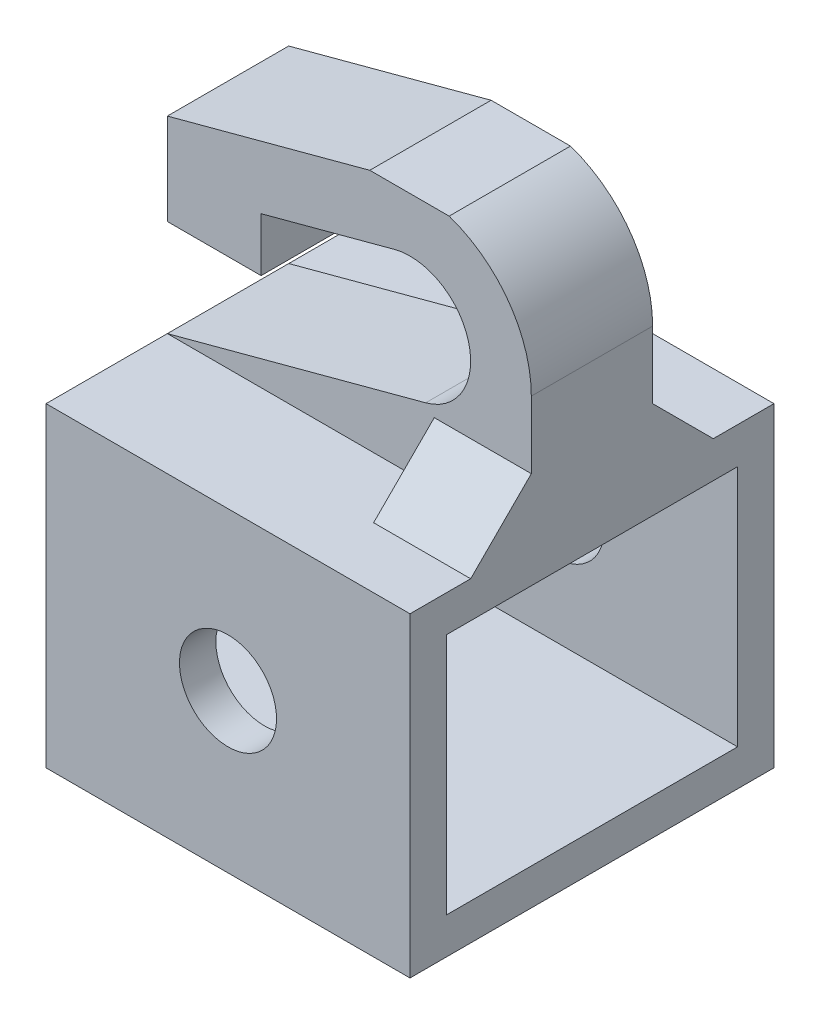
SolidWorks part; units mm, degrees
ref_plane "Front Plane" through (0, 0, 0) normal (0, 0, 1) x (1, 0, 0)
ref_plane "Top Plane" through (0, 0, 0) normal (0, 1, 0) x (1, 0, 0)
ref_plane "Right Plane" through (0, 0, 0) normal (1, 0, 0) x (0, 0, -1)
sketch "Sketch1" plane through (0, 0, 0) normal (0, 1, 0) x (1, 0, 0)
  line L1 (-15, -15) -> (15, -15)
  line L2 (-15, -15) -> (-15, 15)
  line L3 (-15, 15) -> (15, 15)
  line L4 (15, -15) -> (15, 15)
  line L5 (-15, -15) -> (15, 15) construction
  line L6 (-15, 15) -> (15, -15) construction
  point P0 (0, 0)
  dimension "D1" = 30
  dimension "D2" = 30
extrude "Boss-Extrude1" add sketch "Sketch1" along normal blind 26
shell "Shell1" thickness 3
sketch "Sketch3" plane through (0, 0, 15) normal (0, 0, 1) x (1, 0, 0)
  line L0 (-15, 0) -> (15, 26) construction
  line L2 (-15, 26) -> (15, 0) construction
  circle A0 centre (0, 13) radius 4
  dimension "D1" = 8
extrude "Cut-Extrude1" cut sketch "Sketch3" against normal through all
sketch "Sketch4" plane through (0, 0, 0) normal (1, 0, 0) x (0, 0, -1)
  line L0 (-5, 26) -> (5, 26)
  line L1 (5, 26) -> (5, 46)
  line L2 (5, 46) -> (-5, 46)
  line L3 (-5, 46) -> (-5, 26)
  line L6 (-5, 26) -> (5, 46) construction
  line L7 (-5, 46) -> (5, 26) construction
  line L8 (-15, 26) -> (15, 26) construction
  point P4 (0, 36)
  dimension "D1" = 10
  dimension "D3" = 20
extrude "Boss-Extrude4" add sketch "Sketch4" along normal up to surface and the other way up to surface
sketch "Sketch6" plane through (0, 0, -5) normal (0, 0, -1) x (-1, 0, 0)
  line L0 (15, 26) -> (15, 36.3528)
  line L1 (15, 46) -> (15, 26) construction
  line L2 (15, 36.3528) -> (-3.7059, 41.365)
  line L4 (-6.2941, 31.7057) -> (15, 26)
  line L5 (-15, 46) -> (-15, 26) construction
  line L6 (-6.2941, 31.7057) -> (-3.7059, 41.365) construction
  line L7 (-15, 26) -> (15, 26) construction
  arc A0 (-3.7059, 41.365) -> (-6.2941, 31.7057) centre (-5, 36.5354) ccw
  point P10 (0, 0)
  point P13 (-5, 36.5354)
  dimension "D2" = 5
  dimension "D1" = 10
  dimension "D3" = 10
  dimension "D4" = 15
extrude "Cut-Extrude2" cut sketch "Sketch6" against normal blind 10
ref_plane "Plane1" through (15, 0, 0) normal (1, 0, 0) x (0, 0, -1)
sketch "Sketch7" plane through (15, 0, 0) normal (1, 0, 0) x (0, 0, -1)
  line L0 (5, 31) -> (10, 26)
  line L1 (5, 46) -> (5, 26) construction
  line L2 (5, 26) -> (15, 26) construction
  dimension "D1" = 5
rib "Rib1" sketch "Sketch7" sketch "Sketch7" thickness 8 extrusion direction parallel to sketch draft on no parameters "D1"=8
mirror "Mirror1" about plane through (0, 0, 0) normal (0, 0, 1) of "Rib1"
sketch "Sketch8" plane through (0, 0, -5) normal (0, 0, -1) x (-1, 0, 0)
  line L0 (15, 41.5291) -> (-1.6855, 46)
  line L1 (15, 46) -> (15, 36.3528) construction
  line L2 (-15, 46) -> (15, 46) construction
  line L3 (15, 36.3528) -> (-3.7059, 41.365) construction
  line L4 (-1.6855, 46) -> (15, 46)
  line L5 (15, 46) -> (15, 41.5291)
  dimension "D1" = 5
extrude "Cut-Extrude3" cut sketch "Sketch8" against normal blind 10
sketch "Sketch9" plane through (0, 0, -5) normal (0, 0, -1) x (-1, 0, 0)
  line L0 (-15, 46) -> (-1.6855, 46) construction
  line L1 (-15, 46) -> (-15, 31) construction
  line L2 (-15, 36.5354) -> (-15, 46)
  line L3 (-15, 46) -> (-8.2281, 46)
  arc A0 (-8.2281, 46) -> (-15, 36.5354) centre (-5, 36.5354) ccw
extrude "Cut-Extrude4" cut sketch "Sketch9" against normal blind 10
ref_plane "Plane2" through (0, 34, 0) normal (0, 1, 0) x (1, 0, 0)
sketch "Sketch11" plane through (-10.093, 37.6676, 0) normal (0.2588, -0.9659, 0) x (0.9659, 0.2588, 0)
  line L0 (-5.0801, -5) -> (2.9199, -5)
  line L1 (-5.0801, 5) -> (-5.0801, -5) construction
  line L2 (-5.0801, -5) -> (14.2857, -5) construction
  line L3 (2.9199, -5) -> (2.9199, 5)
  line L4 (-5.0801, 5) -> (14.2857, 5) construction
  line L5 (2.9199, 5) -> (-5.0801, 5)
  line L6 (-5.0801, 5) -> (-5.0801, -5)
  point P9 (0, 0)
  dimension "D1" = 8
extrude "Boss-Extrude5" add sketch "Sketch11" along direction (0, -1, 0) on the side of the normal up to surface (4.4233 mm away) up to plane "Plane2"
